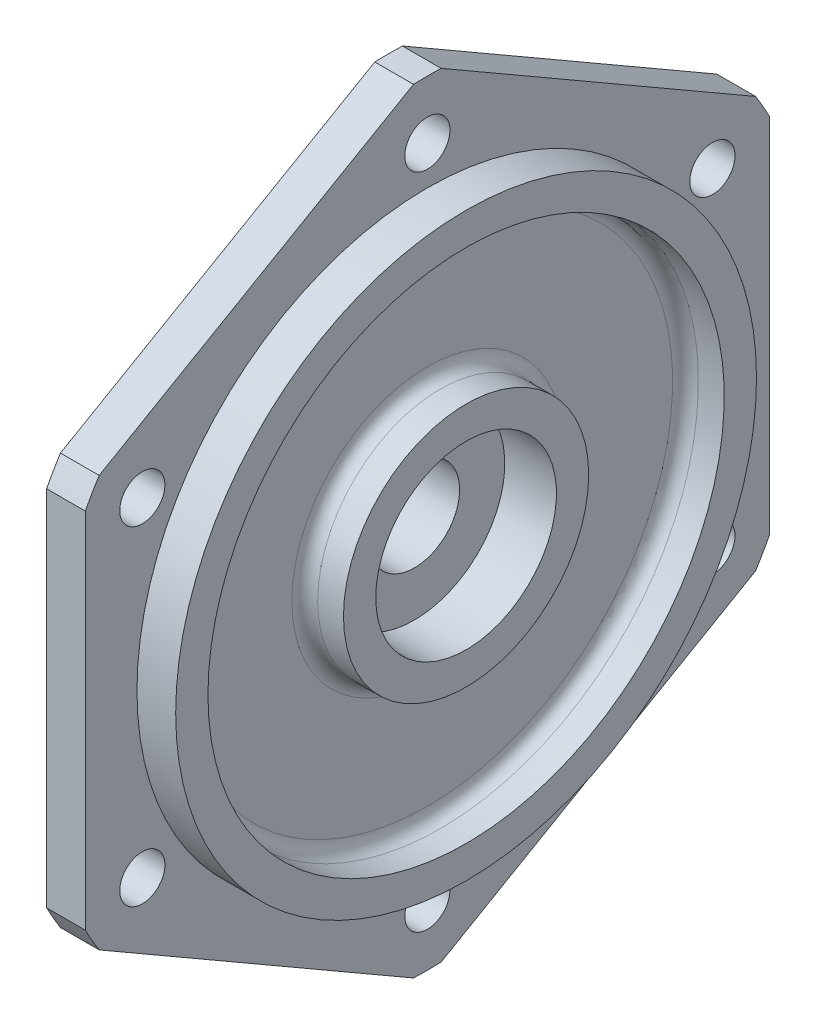
SolidWorks part; units mm, degrees
ref_plane "Front Plane" through (0, 0, 0) normal (0, 0, 1) x (1, 0, 0)
ref_plane "Top Plane" through (0, 0, 0) normal (0, 1, 0) x (1, 0, 0)
ref_plane "Right Plane" through (0, 0, 0) normal (1, 0, 0) x (0, 0, -1)
sketch "Sketch1" plane through (0, 0, 0) normal (0, 0, 1) x (1, 0, 0)
  line L0 (0, 0) -> (0, 34513.855) construction
  line L1 (0, 0) -> (34513.855, 0) construction
  line L2 (-8, 7) -> (-8, 23)
  line L3 (-8, 23) -> (-4, 23)
  line L4 (-4, 23) -> (-4, 60)
  line L5 (-4, 60) -> (2, 60)
  line L6 (2, 60) -> (2, 45)
  line L7 (2, 45) -> (8, 45)
  line L8 (8, 45) -> (8, 40)
  line L9 (8, 40) -> (2, 40)
  line L10 (2, 40) -> (2, 19)
  line L11 (2, 19) -> (8, 19)
  line L12 (8, 19) -> (8, 14)
  line L13 (8, 14) -> (0, 14)
  line L14 (0, 14) -> (0, 7)
  line L15 (0, 7) -> (-8, 7)
  dimension "D1" = 7
  dimension "D2" = 23
  dimension "D3" = 8
  dimension "D4" = 6
  dimension "D5" = 45
  dimension "D6" = 16
  dimension "D7" = 4
  dimension "D8" = 14
  dimension "D9" = 19
  dimension "D10" = 40
  dimension "D11" = 0
  dimension "D12" = 6
  dimension "D13" = 6
  dimension "D14" = 15
revolve "Revolve1" add sketch "Sketch1" angle 360 about L1
sketch "Sketch2" plane through (2, 0, 0) normal (1, 0, 0) x (0, 0, -1)
  circle A0 centre (0, 0) radius 51 construction
  circle A1 centre (0, 51) radius 3.5
  circle A2 centre (44.1673, 25.5) radius 3.5
  circle A3 centre (44.1673, -25.5) radius 3.5
  circle A4 centre (0, -51) radius 3.5
  circle A5 centre (-44.1673, -25.5) radius 3.5
  circle A6 centre (-44.1673, 25.5) radius 3.5
  point P6 (51.0171, 23.1968)
  point P7 (0, 0)
  point P17 (0, 0)
  dimension "D1" = 102
  dimension "D2" = 7
  dimension "D3" = 6
extrude "Cut-Extrude1" cut sketch "Sketch2" against normal blind 10
fillet "Fillet1" radius 2 3 edges at (-4, 0, 23) (2, 0, 19) (2, 0, 40)
sketch "Sketch3" plane through (-4, 0, 0) normal (-1, 0, 0) x (0, 0, 1)
  line L0 (-53, 30.5996) -> (-35.3333, 61.1991)
  line L1 (0, 61.1991) -> (-53, 30.5996)
  line L2 (-53, 30.5996) -> (-53, -30.5996)
  line L3 (-53, -30.5996) -> (0, -61.1991)
  line L4 (0, -61.1991) -> (53, -30.5996)
  line L5 (53, -30.5996) -> (53, 30.5996)
  line L6 (53, 30.5996) -> (0, 61.1991)
  line L7 (-35.3333, 61.1991) -> (0, 61.1991)
  line L8 (0, 61.1991) -> (47.2928, 56.1315)
  line L9 (47.2928, 56.1315) -> (53, 30.5996)
  line L10 (53, 30.5996) -> (77.6869, -12.1594)
  line L11 (77.6869, -12.1594) -> (53, -30.5996)
  line L12 (0, -61.1991) -> (47.2928, -61.1991)
  line L13 (47.2928, -61.1991) -> (53, -30.5996)
  line L14 (-53, -30.5996) -> (-35.3333, -61.1991)
  line L15 (-35.3333, -61.1991) -> (0, -61.1991)
  circle A0 centre (0, 0) radius 53 construction
  circle M10 centre (0, 0) radius 60
  dimension "D1" = 106
extrude "Cut-Extrude2" cut sketch "Sketch3" against normal blind 10 contours L1 M10 | L6 M10 | L5 M10 | L4 M10 | L3 M10 | L2 M10
